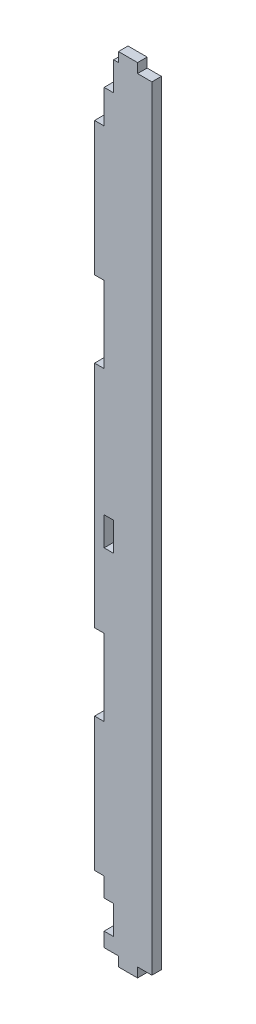
SolidWorks part; units mm, degrees
ref_plane "Front Plane" through (0, 0, 0) normal (0, 0, 1) x (1, 0, 0)
ref_plane "Top Plane" through (0, 0, 0) normal (0, 1, 0) x (1, 0, 0)
ref_plane "Right Plane" through (0, 0, 0) normal (1, 0, 0) x (0, 0, -1)
sketch "Sketch1" plane through (0, 0, 0) normal (0, 0, 1) x (1, 0, 0)
  line L0 (-439.375, -252.5) -> (-422.5, -252.5) construction
  line L6 (-440, -217.5) -> (-440, -177.5)
  line L7 (-440, -217.5) -> (-445, -217.5)
  line L8 (-422.5, -70) -> (-432.5, -70)
  line L9 (-432.5, -70) -> (-432.5, -75)
  line L11 (-422.5, -75) -> (-422.5, -70)
  line L19 (-485.1602, -277.5) -> (-382.7286, -277.5) construction
  line L20 (-422.5, -75) -> (-415, -75)
  line L23 (-432.5, -75) -> (-435, -75)
  line L26 (-440, -107.5) -> (-445, -107.5)
  line L27 (-445, -107.5) -> (-445, -177.5)
  line L28 (-440, -177.5) -> (-445, -177.5)
  line L29 (-440, -217.5) -> (-445, -217.5)
  line L30 (-414.9997, -302.5) -> (-414.9997, -302.4981)
  line L31 (-415, -75) -> (-415, -480)
  line L36 (-440, -107.5) -> (-440, -90)
  line L37 (-427.5, -70) -> (-427.5, -79.2087) construction
  line L38 (-440, -457.5) -> (-435, -457.5)
  line L39 (-415, -337.5) -> (-414.9997, -337.5)
  line L40 (-415, -447.5) -> (-414.9997, -447.5)
  line L41 (-432.5, -265.2975) -> (-432.5, -269.86) construction
  line L42 (-415, -377.5) -> (-414.9997, -377.5)
  line L45 (-415, -217.5) -> (-414.9997, -217.5)
  line L46 (-415, -177.5) -> (-414.9997, -177.5)
  line L48 (-415, -107.5) -> (-414.9997, -107.5)
  line L51 (-415, -217.5) -> (-414.9997, -217.5)
  line L52 (-435, -472.5) -> (-440, -472.5)
  line L53 (-435, -457.5) -> (-435, -472.5)
  line L54 (-414.9997, -252.5) -> (-414.9997, -252.5019)
  line L55 (-415, -337.5) -> (-414.9997, -337.5)
  line L56 (-440, -447.5) -> (-440, -457.5)
  line L57 (-440, -327.5) -> (-445, -327.5) [skipped]
  line L58 (-440, -337.5) -> (-445, -337.5)
  line L59 (-440, -377.5) -> (-445, -377.5)
  line L60 (-445, -447.5) -> (-445, -377.5)
  line L61 (-440, -447.5) -> (-445, -447.5)
  line L62 (-432.5, -480) -> (-440, -480)
  line L64 (-422.5, -480) -> (-415, -480)
  line L65 (-422.5, -480) -> (-422.5, -485)
  line L66 (-432.5, -485) -> (-432.5, -480)
  line L67 (-422.5, -485) -> (-432.5, -485)
  line L68 (-440, -337.5) -> (-445, -337.5)
  line L69 (-440, -337.5) -> (-440, -377.5)
  line L71 (-445, -217.5) -> (-445, -337.5)
  line L72 (-435, -90) -> (-440, -90)
  line L73 (-435, -75) -> (-435, -90)
  line L78 (-440, -283.75) -> (-435, -283.75)
  line L79 (-440, -298.75) -> (-440, -283.75)
  line L92 (-435, -298.75) -> (-440, -298.75)
  line L93 (-435, -283.75) -> (-435, -298.75)
  line L94 (-440, -472.5) -> (-440, -480)
  point P7 (-440, -252.5)
  point P47 (-415, -252.5)
  point P55 (-415, -302.5)
  point P56 (-440, -302.5)
  point P57 (-435, -283.75)
  point P60 (-440, -283.75)
  point P61 (-435, -298.75)
  point P62 (-440, -298.75)
  point P63 (-435, -75)
  point P64 (-435, -90)
  point P65 (-440, -90)
  dimension "D1" = 25
  dimension "D2" = 7.5
  dimension "D3" = 5
  dimension "D4" = 35
  dimension "D6" = 2
  dimension "D7" = 2
extrude "Boss-Extrude1" add sketch "Sketch1" along normal blind 5
